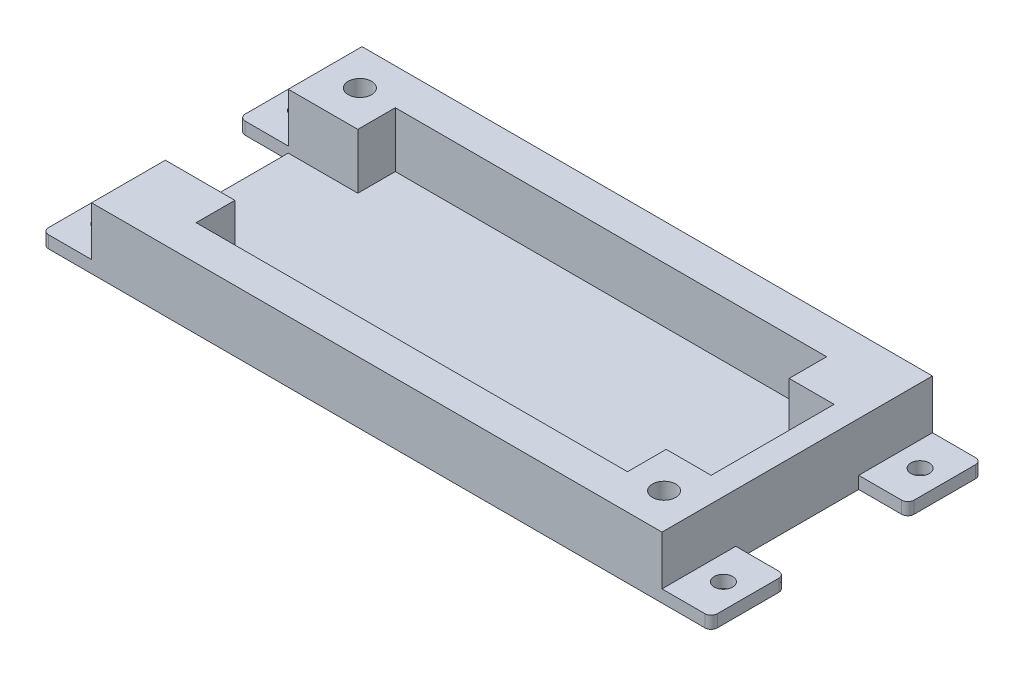
SolidWorks part; units mm, degrees
ref_plane "Plano frontal" through (0, 0, 0) normal (0, 0, 1) x (1, 0, 0)
ref_plane "Plano superior" through (0, 0, 0) normal (0, 1, 0) x (1, 0, 0)
ref_plane "Plano direito" through (0, 0, 0) normal (1, 0, 0) x (0, 0, -1)
sketch "Esboço1" plane through (0, 0, 0) normal (0, 1, 0) x (1, 0, 0)
  line L5 (-21.2, 5) -> (-17.544, 5)
  line L6 (-17.544, 5) -> (-17.544, 8.05)
  line L7 (-17.544, 8.05) -> (17.544, 8.05)
  line L9 (-17.544, -8.15) -> (17.544, -8.15)
  line L11 (17.544, -8.15) -> (17.544, -5)
  line L12 (17.544, -5) -> (21.2, -5)
  line L16 (-21.2, -5) -> (-17.544, -5)
  line L17 (-17.544, -5) -> (-17.544, -8.15)
  line L18 (17.544, 8.05) -> (17.544, 5)
  line L19 (17.544, 5) -> (21.2, 5)
  line L20 (-21.2, 5) -> (-21.2, -5)
  line L21 (21.2, 5) -> (21.2, -5)
  line L23 (-23.2, 11) -> (23.2, 11)
  line L24 (-23.2, 11) -> (-23.2, -11)
  line L25 (-23.2, -11) -> (23.2, -11)
  line L26 (23.2, 11) -> (23.2, -11)
  line L27 (-23.2, 11) -> (23.2, -11) construction
  line L28 (-23.2, -11) -> (23.2, 11) construction
  circle A0 centre (20.372, -8) radius 0.95
  circle A3 centre (-20.372, 8) radius 0.95
  point P0 (0, 0)
  point P6 (0, 0)
  point P7 (0, 0)
  dimension "D5" = 3
  dimension "D6" = 1.9
  dimension "D8" = 1.9
  dimension "D2" = 2.828
  dimension "D3" = 16.2
  dimension "D4" = 2
  dimension "D7" = 2
  dimension "D9" = 3
  dimension "D10" = 2.828
  dimension "D11" = 3
  dimension "D12" = 6
  dimension "D13" = 22
  dimension "D14" = 46.4
  dimension "D16" = 2.828
  dimension "D17" = 2.828
extrude "Ressalto-extrusão1" add sketch "Esboço1" along normal blind 4.5
sketch "Esboço2" plane through (0, 0, 0) normal (0, -1, 0) x (1, 0, 0)
  line L12 (23.2, -11) -> (23.2, 11)
  line L13 (23.2, 11) -> (-23.2, 11)
  line L14 (-23.2, 11) -> (-23.2, -11)
  line L15 (-23.2, -11) -> (23.2, -11)
  line L16 (23.2, -11) -> (23.2, 11)
  line L17 (23.2, 11) -> (-23.2, 11)
  line L18 (-23.2, 11) -> (-23.2, -11)
  line L19 (-23.2, -11) -> (23.2, -11)
  dimension "D1" = 0
extrude "Ressalto-extrusão2" add sketch "Esboço2" along normal blind 0.5
sketch "Esboço4" plane through (0, 0, 0) normal (0, 1, 0) x (1, 0, 0)
  line L0 (23.2, -11) -> (-23.2, -11) construction
  line L1 (23.2, 11) -> (23.2, -11) construction
  line L2 (-23.2, 11) -> (23.2, 11) construction
  circle A4 centre (20.372, -8) radius 1.05
  circle A5 centre (-20.372, 8) radius 1.05
  dimension "D3" = 3
  dimension "D2" = 2.1
  dimension "D6" = 2.1
  dimension "D4" = 2.828
  dimension "D1" = 3
  dimension "D5" = 2.828
extrude "Corte-extrusão2" cut sketch "Esboço4" against normal blind 10.5
sketch "Esboço8" plane through (0, -0.5, 0) normal (0, 1, 0) x (1, 0, 0)
  circle A0 centre (20.372, -8) radius 2
  circle A1 centre (-20.372, 8.05) radius 2
  dimension "D1" = 4
  dimension "D2" = 4
extrude "Corte-extrusão3" cut sketch "Esboço8" along normal blind 3
sketch "Esboço10" plane through (0, 0, 0) normal (0, 1, 0) x (1, 0, 0)
  line L3 (-23.2, 11) -> (-26.7, 11)
  line L14 (-23.2, 5) -> (-26.7, 5)
  line L15 (-23.2, 5) -> (-23.2, 11)
  line L16 (-27.2, 5.5) -> (-27.2, 10.5)
  line L17 (23.2, 11) -> (-23.2, 11) construction
  line L19 (-23.2, 11) -> (-23.2, -11) construction
  line L22 (-23.2, -11) -> (-26.7, -11)
  line L23 (-23.2, -11) -> (-23.2, -5)
  line L24 (-23.2, -5) -> (-26.7, -5)
  line L25 (-27.2, -10.5) -> (-27.2, -5.5)
  line L26 (23.2, 11) -> (26.7, 11)
  line L27 (23.2, 11) -> (23.2, 5)
  line L28 (23.2, 5) -> (26.7, 5)
  line L29 (27.2, 10.5) -> (27.2, 5.5)
  line L30 (23.2, -11) -> (26.7, -11)
  line L31 (23.2, -11) -> (23.2, -5)
  line L32 (23.2, -5) -> (26.7, -5)
  line L33 (27.2, -10.5) -> (27.2, -5.5)
  arc A8 (-26.7, 5) -> (-27.2, 5.5) centre (-26.7, 5.5) cw
  arc A9 (-26.7, 11) -> (-27.2, 10.5) centre (-26.7, 10.5) ccw
  arc A10 (-26.7, -11) -> (-27.2, -10.5) centre (-26.7, -10.5) cw
  arc A11 (-26.7, -5) -> (-27.2, -5.5) centre (-26.7, -5.5) ccw
  arc A12 (26.7, -11) -> (27.2, -10.5) centre (26.7, -10.5) ccw
  arc A13 (26.7, -5) -> (27.2, -5.5) centre (26.7, -5.5) cw
  arc A14 (26.7, 11) -> (27.2, 10.5) centre (26.7, 10.5) cw
  arc A15 (26.7, 5) -> (27.2, 5.5) centre (26.7, 5.5) ccw
  point P27 (27.2, -11)
  point P30 (27.2, -5)
  point P33 (27.2, 11)
  point P36 (27.2, 5)
  point P38 (-27.2, 5)
  point P41 (-27.2, 5)
  point P45 (-27.2, -11)
  point P48 (-27.2, -5)
  dimension "D7" = 4
  dimension "D5" = 0.5
  dimension "D10" = 0.5
  dimension "D12" = 0.5
  dimension "D2" = 6
  dimension "D3" = 6
  dimension "D4" = 4
  dimension "D6" = 6
  dimension "D8" = 6
  dimension "D9" = 4
  dimension "D11" = 4
extrude "Ressalto-extrusão3" add sketch "Esboço10" against normal mid plane 1
sketch "Esboço11" plane through (0, 0.5, 0) normal (0, 1, 0) x (1, 0, 0)
  line L0 (23.2, 11) -> (-23.2, 11) construction
  line L2 (-23.2, -11) -> (23.2, -11) construction
  circle A0 centre (-25.2, 8) radius 0.75
  circle A1 centre (-25.2, -8) radius 0.75
  circle A2 centre (25.2, -8) radius 0.75
  circle A3 centre (25.2, 8) radius 0.75
  dimension "D1" = 1.5
  dimension "D4" = 1.5
  dimension "D6" = 1.5
  dimension "D9" = 1.5
  dimension "D2" = 2
  dimension "D3" = 3
  dimension "D5" = 3
  dimension "D7" = 3
  dimension "D8" = 2
  dimension "D10" = 3
extrude "Corte-extrusão5" cut sketch "Esboço11" against normal blind 10
sketch "Esboço12" plane through (0, 4.5, 0) normal (0, 1, 0) x (1, 0, 0)
  line L0 (17.544, -5) -> (17.544, 5)
  line L1 (17.544, -5) -> (-23.2, -5)
  line L3 (17.544, 5) -> (-23.2, 5)
  line L4 (-23.2, -5) -> (-23.2, 5)
  line L5 (17.544, -3.781) -> (-23.2, 5) construction
  line L6 (17.544, 3.781) -> (-23.2, -5) construction
  line L7 (17.544, 5) -> (17.544, 8.05) construction
  point P0 (0, 0)
extrude "Corte-extrusão6" cut sketch "Esboço12" against normal up to surface (4.5 mm away) up to face at (0, 0, 0.0167)
